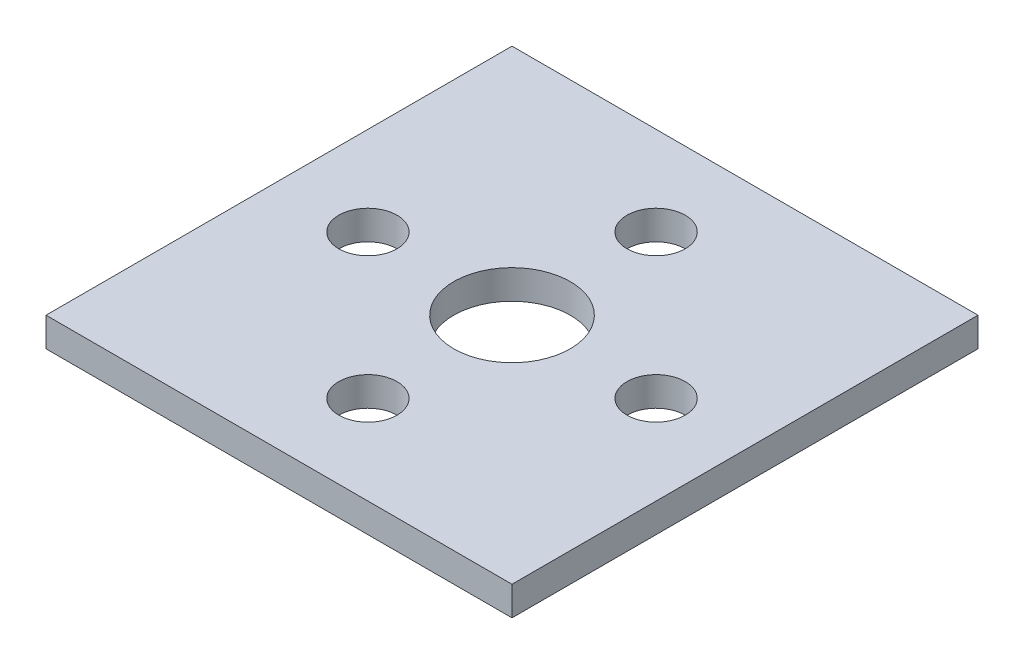
SolidWorks part; units mm, degrees
ref_plane "Front Plane" through (0, 0, 0) normal (0, 0, 1) x (1, 0, 0)
ref_plane "Top Plane" through (0, 0, 0) normal (0, 1, 0) x (1, 0, 0)
ref_plane "Right Plane" through (0, 0, 0) normal (1, 0, 0) x (0, 0, -1)
sketch "Sketch1" plane through (0, 0, 0) normal (0, 1, 0) x (1, 0, 0)
  line L1 (0, 0) -> (50.8, 0)
  line L2 (0, 0) -> (0, 50.8)
  line L3 (0, 50.8) -> (50.8, 50.8)
  line L4 (50.8, 0) -> (50.8, 50.8)
  circle A0 centre (25.4, 25.4) radius 6.35
  circle A1 centre (25.4, 41.1092) radius 3.175
  circle A2 centre (41.1092, 25.4) radius 3.175
  circle A3 centre (25.4, 9.6908) radius 3.175
  circle A4 centre (9.6908, 25.4) radius 3.175
  point P18 (25.4, 25.4)
  dimension "D3" = 12.7
  dimension "D6" = 6.35
  dimension "D1" = 50.8
  dimension "D2" = 50.8
  dimension "D4" = 25.4
  dimension "D5" = 25.4
  dimension "D7" = 25.4
  dimension "D8" = 4
extrude "Boss-Extrude1" add sketch "Sketch1" along normal blind 3.175
